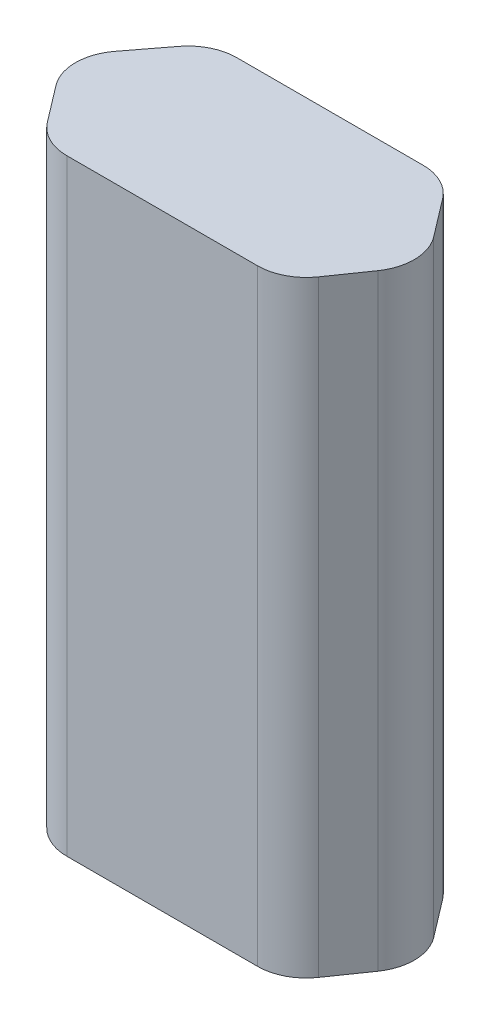
SolidWorks part; units mm, degrees
ref_plane "Front" through (0, 0, 0) normal (0, 0, 1) x (1, 0, 0)
ref_plane "Top" through (0, 0, 0) normal (0, 1, 0) x (1, 0, 0)
ref_plane "Right" through (0, 0, 0) normal (1, 0, 0) x (0, 0, -1)
sketch "Sketch1" plane through (0, 0, 0) normal (0, 1, 0) x (1, 0, 0)
  line L0 (-7.5, 0) -> (7.5, 0) construction
  line L3 (0, 0) -> (0, 3.5) construction
  line L4 (-7.5, 0) -> (-4.8313, 3.5)
  line L5 (-4.8313, 3.5) -> (4.8313, 3.5)
  line L6 (7.5, 0) -> (4.8313, 3.5)
  line L7 (7.5, 0) -> (5.0687, -3.5)
  line L8 (-4.8313, -3.5) -> (5.0687, -3.5)
  line L9 (-7.5, 0) -> (-4.8313, -3.5)
  dimension "D1" = 15
  dimension "D2" = 7
  dimension "D3" = 3.5
  dimension "D4" = 9.9
  dimension "D5" = 127.326
  dimension "D6" = 127.326
extrude "Boss-Extrude1" add sketch "Sketch1" along normal blind 25
fillet "Fillet1" radius 2 6 edges at (5.0687, 12.5, 3.5) (7.5, 12.5, 0) (4.8313, 12.5, -3.5) (-4.8313, 12.5, 3.5) (-4.8313, 12.5, -3.5) (-7.5, 12.5, 0)
